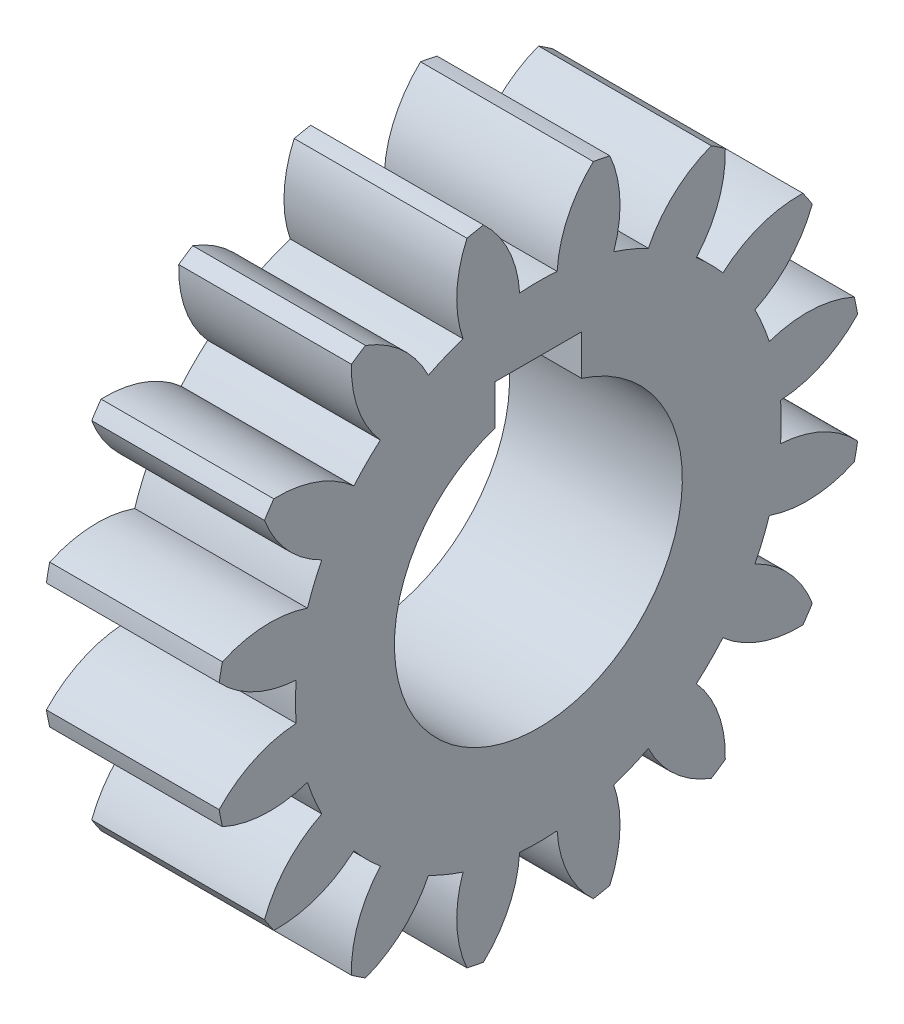
SolidWorks part; units mm, degrees
ref_plane "Plane1" through (0, 0, 0) normal (0, 0, 1) x (1, 0, 0)
ref_plane "Plane2" through (0, 0, 0) normal (0, 1, 0) x (1, 0, 0)
ref_plane "Plane3" through (0, 0, 0) normal (1, 0, 0) x (0, 0, -1)
sketch "HoldingSke" plane through (0, 0, 0) normal (0, 1, 0) x (1, 0, 0)
  line L0 (0, 0) -> (0.769, -0.2205)
  line L1 (-15, 0) -> (100, 0) construction
  line L2 (0, 0) -> (-2.1039, 2.3779)
  line L3 (0, 0) -> (-11.863, 4.5341)
  line L4 (0, 0) -> (8.3015, 2.3804)
  line L5 (0, 0) -> (-46.8476, -17.4728)
  line L6 (0, 0) -> (-4.1448, -2.7965)
  line L7 (-2.1039, 2.3779) -> (8.6586, 51.2059)
  line L8 (-76.2, 54.61) -> (-76.1, 54.61)
  line L9 (-71.009, 38.7566) -> (-53.1078, 45.2721)
  line L10 (-76.2, 71.12) -> (104.1128, 71.12)
  line L11 (0, 0) -> (-5, 0)
  line L12 (-76.2, 101.6) -> (-76.155, 101.6)
  line L13 (24.9733, 27.94) -> (52.9518, 28.4284)
  line L14 (24.9733, 27.94) -> (24.9743, 27.94)
  line L15 (24.9733, 27.94) -> (100.4006, 29.5858)
  line L16 (-63.627, -1.25) -> (-12.827, -1.25)
  circle A0 centre (0, 0) radius 0.4
  circle A1 centre (0, 0) radius 8.4365
  circle A2 centre (0, 0) radius 37.5
  circle A3 centre (0, 0) radius 0.4
  dimension "MHD" = 16.873
  dimension "Hub_dia" = 75
  dimension "Bore" = 0.8
  dimension "MBD" = 0.8
  dimension "Num_teeth" = 16
  dimension "Pitch" = 0.8
  dimension "Overall_len" = 50
  dimension "Show_teeth" = 16
  dimension "Thickness" = 5
  dimension "OAL" = 50.0001
  dimension "T_dim" = 0.1
  dimension "Ap" = 20
  dimension "H" = 19.05
  dimension "Pitch_radius" = 180.3128
  dimension "Width" = 5
  dimension "Backlash" = 0.045
  dimension "Addendum_fac" = 1
  dimension "Dedendum_fac" = 1.25
  dimension "Clearance_fac" = 0.25
  dimension "Dedendum_add" = 0.001
  dimension "Module" = 1.25
sketch "BasProSke" plane through (0, 0, 0) normal (0, 1, 0) x (1, 0, 0)
  line L0 (-10, 0) -> (60, 0) construction
  line L1 (0, 0) -> (0, 11.25)
  line L2 (0, 0) -> (6, 0)
  line L3 (6, 0) -> (6, 11.25)
  line L4 (6, 11.25) -> (0, 11.25)
  dimension "Thickness" = 6
  dimension "Diameter" = 22.5
revolve "Base-Revolve" add sketch "BasProSke" angle 360 about L0
sketch "TooCutSke" plane through (0, 0, 0) normal (1, 0, 0) x (0, 0, -1)
  line L1 (0, 0) -> (0, 107) construction
  line L2 (0, 0) -> (-1.0589, 9.9438) construction
  line L3 (0, 0) -> (-3.8859, 19.5358) construction
  line L4 (-1.0589, 9.9438) -> (-1.943, 9.7679) construction
  arc A0 (0.6511, 8.4113) -> (-0.6511, 8.4113) centre (0, 0) ccw
  arc A1 (1.9309, 11.1088) -> (-1.9309, 11.1088) centre (0, 0) ccw
  circle A2 centre (0, 0) radius 10 construction
  circle A3 centre (0, 0) radius 9.3969 construction
  arc A4 (-0.6511, 8.4113) -> (-1.9309, 11.1088) centre (-4.6437, 8.1693) ccw
  arc A5 (1.9309, 11.1088) -> (0.6511, 8.4113) centre (4.6437, 8.1693) ccw
  dimension "Root_dia" = 16.873
  dimension "Overcut_dia" = 22.5508
  dimension "Pitch_dia" = 20
  dimension "Base_dia" = 18.7939
  dimension "Flank_rad" = 4
  dimension "Half_ang" = 11.25
  dimension "Half_CT" = 0.9014
extrude "ToothCut" cut sketch "TooCutSke" along normal through all
fillet "Breaks" [suppressed] radius 0.025
fillet "RootFillets" [suppressed] radius 0.3135
pattern_circular "TeethCuts" count 16 every 22.5 about axis through (-10, 0, 0) along (1, 0, 0) of "ToothCut", "RootFillets", "Breaks"
sketch "HubNeaOneSke" plane through (0, 0, 0) normal (-1, 0, 0) x (0, 0, 1)
  circle A0 centre (0, 0) radius 8.4365
  dimension "Diameter" = 16.873
extrude "HubNearOne" [suppressed] add sketch "HubNeaOneSke" along normal blind 44.0001
sketch "HubNeaBotSke" plane through (0, 0, 0) normal (-1, 0, 0) x (0, 0, 1)
  circle A0 centre (0, 0) radius 8.4365
  dimension "Diameter" = 16.873
extrude "HubNearBoth" [suppressed] add sketch "HubNeaBotSke" along normal blind 22
ref_plane "FarPln" through (6, 0, 0) normal (1, 0, 0) x (0, 0, -1)
sketch "HubFarSke" plane through (6, 0, 0) normal (1, 0, 0) x (0, 0, -1)
  circle A0 centre (0, 0) radius 8.4365
  dimension "Diameter" = 16.873
extrude "HubFar" [suppressed] add sketch "HubFarSke" along normal blind 22
sketch "BorSke" plane through (0, 0, 0) normal (1, 0, 0) x (0, 0, -1)
  circle A0 centre (0, 0) radius 0.4
  dimension "Diameter" = 0.8
extrude "Bore" cut sketch "BorSke" along normal mid plane 100.0001
sketch "KeySke" plane through (0, 0, 0) normal (1, 0, 0) x (0, 0, -1)
  line L0 (-0.05, 0) -> (-0.05, 0.5)
  line L1 (-0.05, 0.5) -> (0.05, 0.5)
  line L2 (0.05, 0.5) -> (0.05, 0)
  line L3 (0, 0) -> (0, 34) construction
  line L4 (-0.05, 0) -> (0.05, 0)
  dimension "Offset" = 0.5
  dimension "Width" = 0.1
extrude "Keyway" [suppressed] cut sketch "KeySke" along normal mid plane 100.0001
pattern_circular "Keyway2" [suppressed] count 2 every 90 about axis through (-10, 0, 0) along (1, 0, 0)
sketch "Schizzo1" plane through (6, 0, 0) normal (1, 0, 0) x (0, 0, -1)
  line L0 (0, 0) -> (0, 11.6297) construction
  line L1 (1.5, 4.7697) -> (1.5, 6.1697)
  line L2 (1.5, 6.1697) -> (-1.5, 6.1697)
  line L3 (-1.5, 6.1697) -> (-1.5, 4.7697)
  circle A0 centre (0, 0) radius 5
  point P10 (0, 6.1697)
  dimension "D1" = 10
  dimension "D2" = 3
  dimension "D3" = 1.4
extrude "Taglio-Estrusione1" cut sketch "Schizzo1" against normal blind 10
equation "' \"Module@HoldingSke\" = 6.35"
equation "' \"Num_teeth@HoldingSke\" = 12"
equation "' \"Ap@HoldingSke\" =  20"
equation "' \"Ap@HoldingSke\" = 20"
equation "' \"Width@HoldingSke\" = 0.5 * 25.4"
equation "' \"Hub_dia@HoldingSke\"= 1 * 25.4"
equation "' \"Hub_dia@HoldingSke\" = 1 * 25.4"
equation "' \"Overall_len@HoldingSke\" = 1.0 * 25.4"
equation "' \"Bore@HoldingSke\" = 0.75 * 25.4"
equation "' \"T_dim@HoldingSke\" = 0.1 * 25.4"
equation "' \"Width@KeySke\" = 0.25 * 25.4"
equation "' \"Show_teeth@HoldingSke\" = 13"
equation "' \"Backlash@HoldingSke\" = 0.009 * 25.4"
equation "' \"Addendum_fac@HoldingSke\" = 1.0"
equation "' \"Dedendum_fac@HoldingSke\" = 1.25"
equation "' \"Dedendum_add@HoldingSke\" = 0.00005 * 25.4"
equation "' \"Clearance_fac@HoldingSke\" = 0.25"
equation "\"Pitch@HoldingSke\" = 1 / \"Module@HoldingSke\""
equation "\"Overcut_dia@TooCutSke\" = (\"Num_teeth@HoldingSke\" + 2 * \"Addendum_fac@HoldingSke\") / \"Pitch@HoldingSke\" + 0.002 * 25.4"
equation "\"Pitch_dia@TooCutSke\" = \"Num_teeth@HoldingSke\" / \"Pitch@HoldingSke\""
equation "\"Base_dia@TooCutSke\" = \"Num_teeth@HoldingSke\" / \"Pitch@HoldingSke\" * cos((\"Ap@HoldingSke\"  * 3.14159265 / 180))"
equation "\"Root_dia@TooCutSke\" = (\"Num_teeth@HoldingSke\" + 2) / \"Pitch@HoldingSke\" - 2 * (\"Addendum_fac@HoldingSke\" + \"Dedendum_fac@HoldingSke\") / \"Pitch@HoldingSke\" - \"Dedendum_add@HoldingSke\" * 2"
equation "\"Half_ang@TooCutSke\" = 180 / \"Num_teeth@HoldingSke\""
equation "\"Half_CT@TooCutSke\" = \"Num_teeth@HoldingSke\" / \"Pitch@HoldingSke\" * sin((3.14159265 / 2 / \"Num_teeth@HoldingSke\")) / 2 - 7 * \"Backlash@HoldingSke\" / 4"
equation "\"Flank_rad@TooCutSke\" = \"Num_teeth@HoldingSke\" / \"Pitch@HoldingSke\" / 5"
equation "\"Radius@RootFillets\" = \"Clearance_fac@HoldingSke\" / \"Pitch@HoldingSke\" + \"Dedendum_add@HoldingSke\""
equation "\"Break_rad@Breaks\" = 0.02 / \"Pitch@HoldingSke\""
equation "\"Thickness@HoldingSke\" = \"Width@HoldingSke\""
equation "\"OAL@HoldingSke\" = \"Thickness@HoldingSke\""
equation "\"MHD@HoldingSke\" = (\"Num_teeth@HoldingSke\" + 2) / \"Pitch@HoldingSke\" - 2 * (\"Addendum_fac@HoldingSke\" + \"Dedendum_fac@HoldingSke\")  / \"Pitch@HoldingSke\" - \"Dedendum_add@HoldingSke\" * 2"
equation "\"MBD@HoldingSke\" = (\"Num_teeth@HoldingSke\" + 2) / \"Pitch@HoldingSke\" - 2 * (\"Addendum_fac@HoldingSke\" + \"Dedendum_fac@HoldingSke\")  / \"Pitch@HoldingSke\" - \"Dedendum_add@HoldingSke\" * 2 - 0.002 * 25.4"
equation "\"MHD@HoldingSke\" = ((sgn( \"MHD@HoldingSke\" - \"Hub_dia@HoldingSke\" )-1)*( \"MHD@HoldingSke\" - \"Hub_dia@HoldingSke\" ))/-2+ \"Hub_dia@HoldingSke\""
equation "\"MBD@HoldingSke\" = ((sgn( \"MBD@HoldingSke\" - \"Bore@HoldingSke\" )-1)*( \"MBD@HoldingSke\" - \"Bore@HoldingSke\" ))/-2+ \"Bore@HoldingSke\""
equation "\"OAL@HoldingSke\" = ((sgn( \"OAL@HoldingSke\" - \"Overall_len@HoldingSke\" )+1)*( \"OAL@HoldingSke\" - \"Overall_len@HoldingSke\" ))/2 + \"Overall_len@HoldingSke\" + 0.000002 * 25.4"
equation "\"Num_teeth@TeethCuts\" = int( \"Show_teeth@HoldingSke\" ) + 1"
equation "\"Num_teeth@TeethCuts\" = ((sgn( \"Num_teeth@TeethCuts\" - \"Num_teeth@HoldingSke\" )-1)*( \"Num_teeth@TeethCuts\" - \"Num_teeth@HoldingSke\" ))/-2+ \"Num_teeth@HoldingSke\""
equation "\"Num_teeth@TeethCuts\" = ((sgn( \"Num_teeth@TeethCuts\" - 2.0)+1)*( \"Num_teeth@TeethCuts\" - 2.0))/2 +2.0"
equation "\"Angle@TeethCuts\" = 360.0 / \"Num_teeth@HoldingSke\""
equation "\"Diameter@BasProSke\" = (\"Num_teeth@HoldingSke\" + 2 * \"Addendum_fac@HoldingSke\") / \"Pitch@HoldingSke\""
equation "\"Thickness@BasProSke\"=6"
equation "' \"Fillet_rad@BasProSke\" =  \"Thickness@HoldingSke\" * 0.05"
equation "' \"Fillet_rad@BasProSke\" = \"Thickness@HoldingSke\" * 0.05"
equation "\"MHD@HoldingSke\" = ((sgn( \"MHD@HoldingSke\" - \"Root_dia@TooCutSke\" )-1)*( \"MHD@HoldingSke\" - \"Root_dia@TooCutSke\" ))/-2+ \"Root_dia@TooCutSke\""
equation "\"Diameter@HubNeaOneSke\" = \"MHD@HoldingSke\""
equation "\"Length@HubNearOne\" = \"OAL@HoldingSke\" - \"Thickness@BasProSke\""
equation "\"Diameter@HubNeaBotSke\" = \"MHD@HoldingSke\""
equation "\"Length@HubNearBoth\" = ( \"OAL@HoldingSke\" - \"Thickness@BasProSke\" ) / 2.0"
equation "\"Thickness@FarPln\" = \"Thickness@BasProSke\""
equation "\"Diameter@HubFarSke\" = \"MHD@HoldingSke\""
equation "\"Length@HubFar\" = ( \"OAL@HoldingSke\" - \"Thickness@BasProSke\" ) / 2.0"
equation "\"Diameter@BorSke\" = \"MBD@HoldingSke\""
equation "\"D1@Bore\" = \"OAL@HoldingSke\" * 2.0"
equation "\"D1@Keyway\" = \"OAL@HoldingSke\" * 2.0"
equation "\"Offset@KeySke\" = \"T_dim@HoldingSke\" + \"MBD@HoldingSke\" / 2.0"
